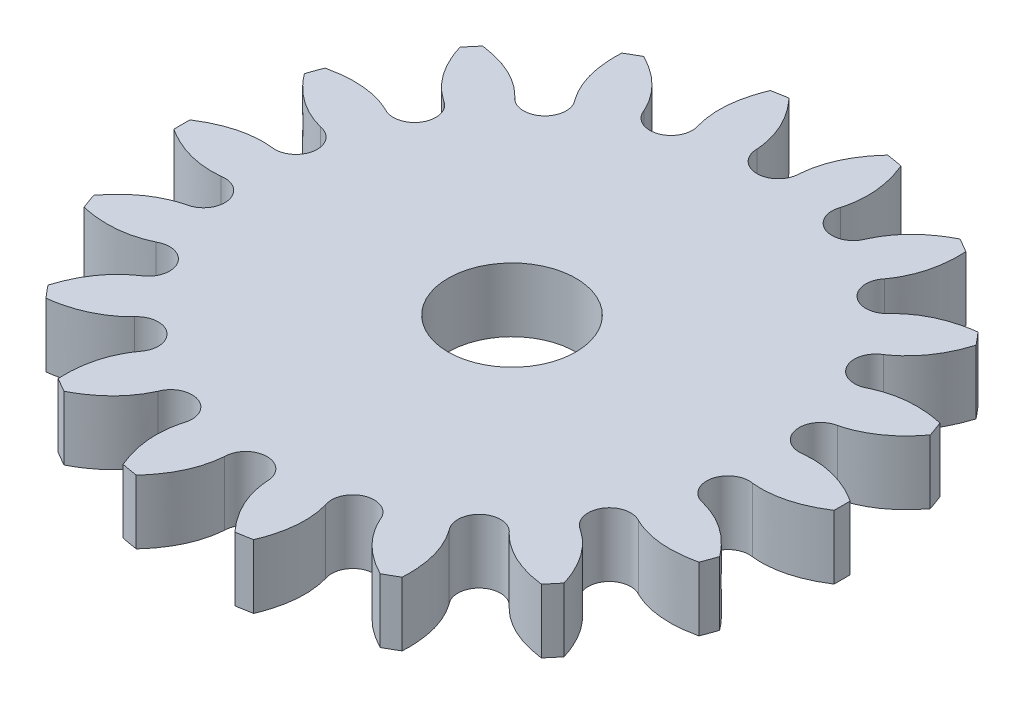
SolidWorks part; units mm, degrees
ref_plane "Front Plane" through (0, 0, 0) normal (0, 0, 1) x (1, 0, 0)
ref_plane "Top Plane" through (0, 0, 0) normal (0, 1, 0) x (1, 0, 0)
ref_plane "Right Plane" through (0, 0, 0) normal (1, 0, 0) x (0, 0, -1)
sketch "Sketch1" plane through (0, 0, 0) normal (0, 1, 0) x (1, 0, 0)
  circle A0 centre (0, 0) radius 3
  circle A1 centre (0, 0) radius 15.5
extrude "Boss-Extrude1" add sketch "Sketch1" along normal blind 3
sketch "Sketch3" plane through (0, 3, 0) normal (0, 1, 0) x (1, 0, 0)
  line L0 (0, 12.5) -> (0, 15.5) construction
  circle A0 centre (0, 0) radius 12.5 construction
  arc A1 (-1, 12.5) -> (1, 12.5) centre (0, 12.5) ccw
  circle A2 centre (0, 0) radius 15.5 construction
  arc A3 (2.317, 15.3258) -> (-2.317, 15.3258) centre (0, 0) ccw
  spline S0 degree 2 poles (-2.317, 15.3258) (-1.1176, 14.0328) (-1, 12.5) knots 0 0 0 0.821337 0.821337 0.821337
  spline S1 degree 2 poles (2.317, 15.3258) (1.1176, 14.0328) (1, 12.5) knots 0 0 0 0.821337 0.821337 0.821337
extrude "Cut-Extrude3" cut sketch "Sketch3" against normal blind 3
pattern_circular "CirPattern2" count 18 over 360 about axis through (0, 3, 0) along (0, 1, 0) of "Cut-Extrude3"
